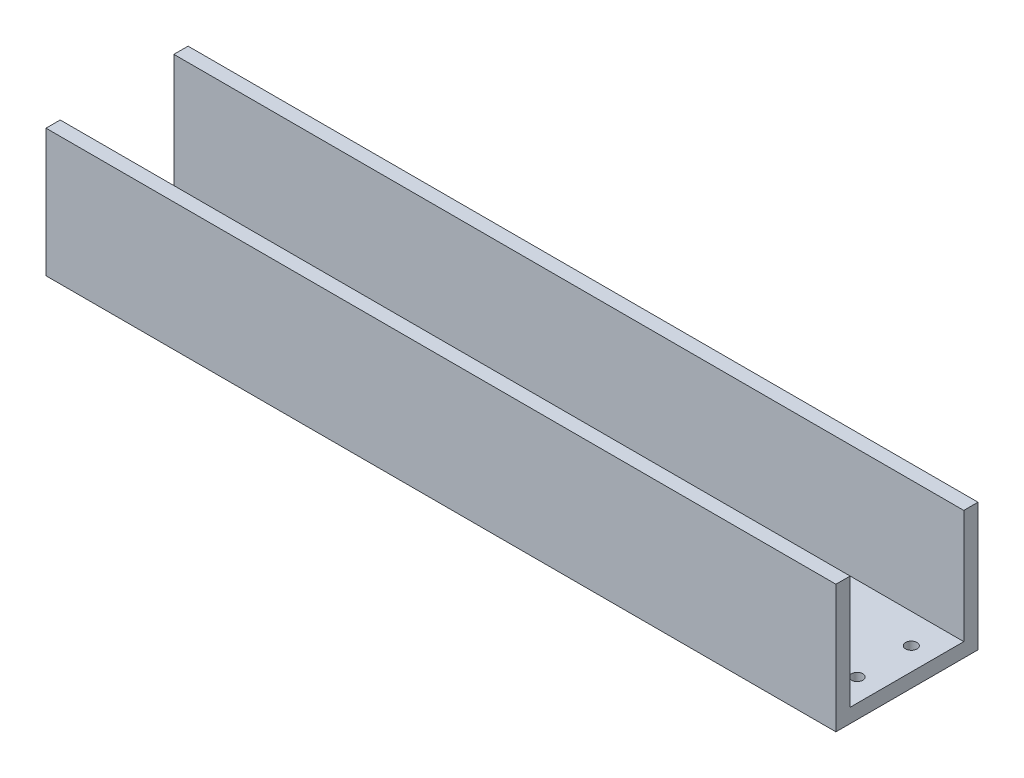
SolidWorks part; units mm, degrees
ref_plane "Front Plane" through (0, 0, 0) normal (0, 0, 1) x (1, 0, 0)
ref_plane "Top Plane" through (0, 0, 0) normal (0, 1, 0) x (1, 0, 0)
ref_plane "Right Plane" through (0, 0, 0) normal (1, 0, 0) x (0, 0, -1)
sketch "Sketch1" plane through (0, 0, 0) normal (1, 0, 0) x (0, 0, -1)
  line L0 (0, 0) -> (50, 0)
  line L1 (50, 0) -> (50, 45)
  line L2 (50, 45) -> (45, 45)
  line L3 (45, 45) -> (45, 5)
  line L4 (45, 5) -> (5, 5)
  line L5 (5, 5) -> (5, 45)
  line L6 (5, 45) -> (0, 45)
  line L7 (0, 45) -> (0, 0)
  dimension "D1" = 40
  dimension "D2" = 5
  dimension "D3" = 5
  dimension "D4" = 40
extrude "Boss-Extrude1" add sketch "Sketch1" along normal blind 278
sketch "Sketch2" plane through (0, 5, 0) normal (0, 1, 0) x (1, 0, 0)
  line L0 (139, 25) -> (139, 16.4145) construction
  line L1 (0, 45) -> (0, 5) construction
  line L2 (0, 0) -> (0, 50) construction
  line L3 (0, 25) -> (278, 25) construction
  line L4 (278, 45) -> (278, 5) construction
  circle A0 centre (8, 15.475) radius 2
  circle A1 centre (55, 15.475) radius 2
  circle A2 centre (55, 34.525) radius 2
  circle A3 centre (8, 34.525) radius 2
  circle A4 centre (270, 34.525) radius 2
  circle A5 centre (223, 34.525) radius 2
  circle A6 centre (223, 15.475) radius 2
  circle A7 centre (270, 15.475) radius 2
  point P6 (139, 25)
  point P27 (0, 0)
  point P28 (102.4347, 25)
  dimension "D1" = 4
  dimension "D2" = 4
  dimension "D3" = 47
  dimension "D4" = 9.525
  dimension "D5" = 8
  dimension "D6" = 139
extrude "Cut-Extrude3" cut sketch "Sketch2" against normal up to next
equation "\"D3@Sketch1\"=\"D2@Sketch1\""
equation "\"D1@Boss-Extrude1\"=(32+57)*2 + 100"
equation "\"D2@Sketch2\"=\"D1@Sketch2\""
